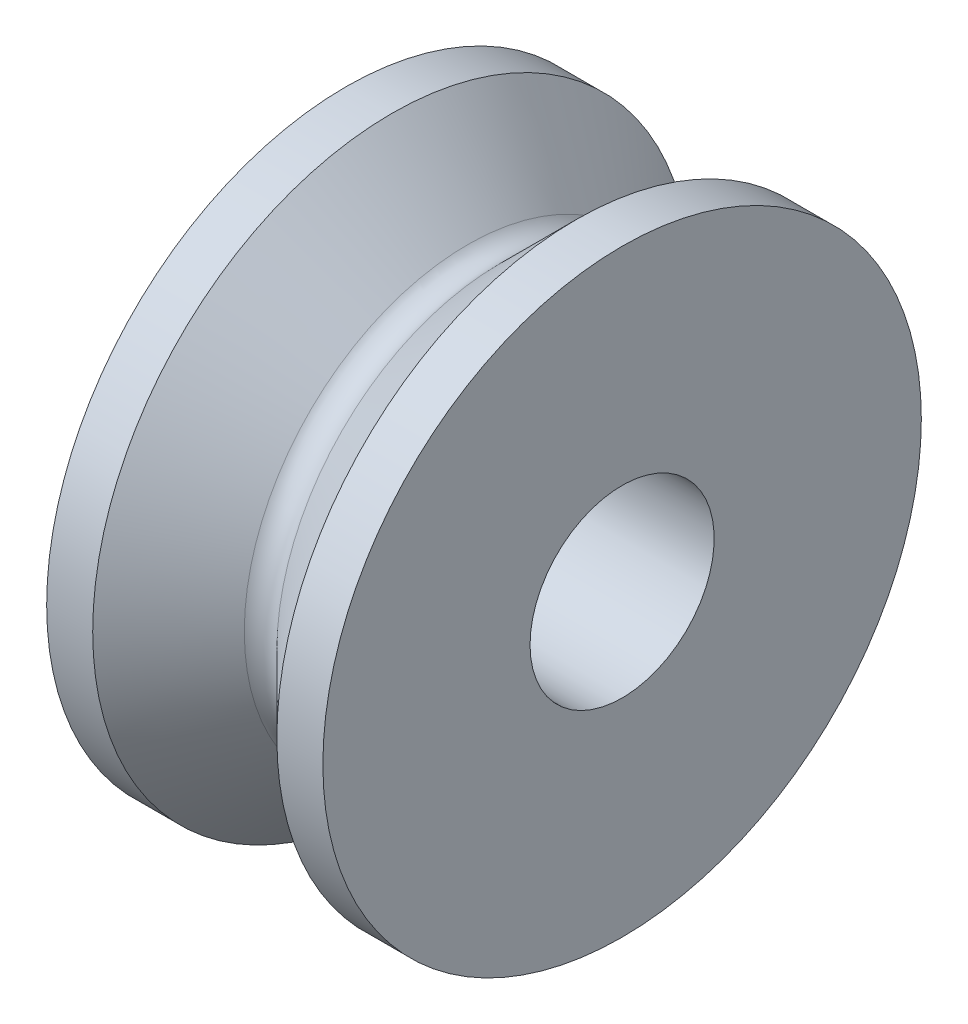
SolidWorks part; units mm, degrees
ref_plane "前视基准面" through (0, 0, 0) normal (0, 0, 1) x (1, 0, 0)
ref_plane "上视基准面" through (0, 0, 0) normal (0, 1, 0) x (1, 0, 0)
ref_plane "右视基准面" through (0, 0, 0) normal (1, 0, 0) x (0, 0, -1)
sketch "草图1" plane through (0, 0, 0) normal (0, 0, 1) x (1, 0, 0)
  line L0 (-66.4317, 0) -> (54.3015, 0) construction
  line L1 (0, 67.3864) -> (0, -55.2421) construction
  line L2 (0, 2) -> (-3, 2)
  line L3 (-3, 2) -> (-3, 6.5)
  line L4 (-3, 6.5) -> (-2, 6.5)
  line L5 (-2, 6.5) -> (0, 4.5)
  line L6 (0, 4.5) -> (0, 2)
  dimension "D1" = 3
  dimension "D2" = 4.5
  dimension "D3" = 1
  dimension "D4" = 2
  dimension "D5" = 2
revolve "旋转1" add sketch "草图1" angle 360 about L0
mirror "镜向1" about plane through (0, 0, 0) normal (1, 0, 0) of "旋转1"
fillet "圆角1" radius 0.5 1 edges at (0, 0, 4.5)
